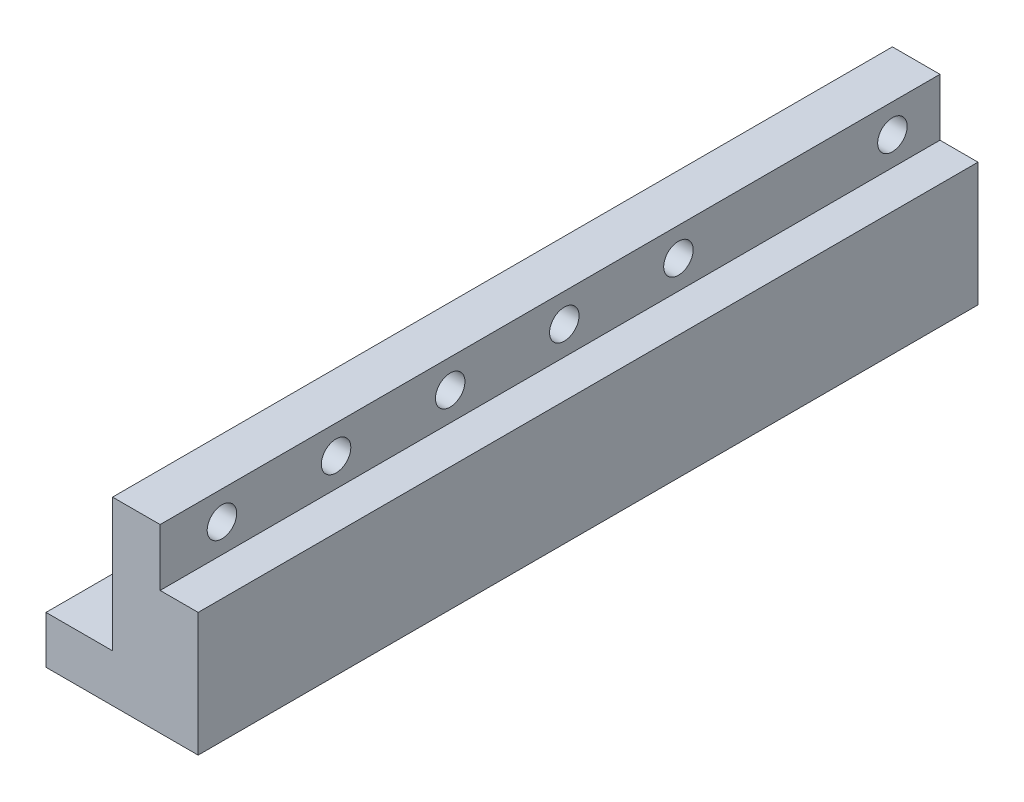
SolidWorks part; units mm, degrees
ref_plane "前基準面" through (0, 0, 0) normal (0, 0, 1) x (1, 0, 0)
ref_plane "上基準面" through (0, 0, 0) normal (0, 1, 0) x (1, 0, 0)
ref_plane "右基準面" through (0, 0, 0) normal (1, 0, 0) x (0, 0, -1)
sketch "草圖1" plane through (0, 0, 0) normal (0, 0, 1) x (1, 0, 0)
  line L0 (-9, 6) -> (-9, -8)
  line L1 (-9, -8) -> (-16, -8)
  line L2 (-16, -8) -> (-16, -13)
  line L3 (-16, -13) -> (0, -13)
  line L4 (0, -13) -> (0, 0)
  line L5 (0, 0) -> (-4, 0)
  line L6 (-4, 0) -> (-4, 6)
  line L7 (-4, 6) -> (-9, 6)
  dimension "D1" = 5
  dimension "D2" = 5
  dimension "D3" = 4
  dimension "D4" = 6
  dimension "D5" = 14
  dimension "D6" = 7
extrude "填料-伸長1" add sketch "草圖1" along normal blind 82
sketch "草圖2" plane through (-4, 0, 0) normal (1, 0, 0) x (0, 0, -1)
  line L0 (-82, 3) -> (0, 3) construction
  line L1 (-82, 0) -> (-82, 6) construction
  line L2 (0, 0) -> (0, 6) construction
  circle A0 centre (-75.5, 3) radius 1.55
  circle A1 centre (-63.5, 3) radius 1.55
  circle A2 centre (-51.5, 3) radius 1.55
  circle A3 centre (-39.5, 3) radius 1.55
  circle A4 centre (-27.5, 3) radius 1.55
  circle A5 centre (-5, 3) radius 1.55
  dimension "D1" = 3.1
  dimension "D2" = 3.1
  dimension "D3" = 3.1
  dimension "D4" = 3.1
  dimension "D5" = 3.1
  dimension "D6" = 3.1
  dimension "D7" = 6.5
  dimension "D8" = 12
  dimension "D9" = 12
  dimension "D10" = 12
  dimension "D11" = 12
  dimension "D12" = 5
extrude "除料-伸長1" cut sketch "草圖2" against normal through all
sketch "草圖3" plane through (0, -8, 0) normal (0, 1, 0) x (1, 0, 0)
  line L2 (-9, 0) -> (-16, 0) construction
  circle A0 centre (-12.5, -11) radius 1.55
  point P0 (-12.5, 0)
  dimension "D2" = 3.1
  dimension "D1" = 11
extrude "除料-伸長2" cut sketch "草圖3" against normal through all
pattern_linear "直線複製排列1" count 5 spacing 15 along (0, 0, 1) of "除料-伸長2"
